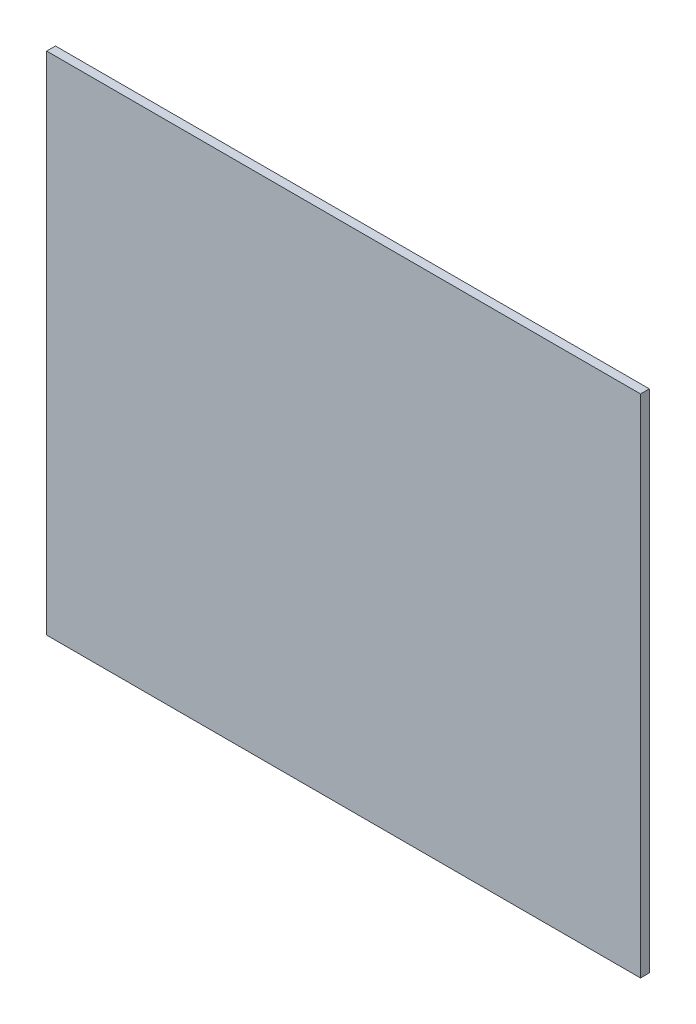
SolidWorks part; units mm, degrees
ref_plane "Front Plane" through (0, 0, 0) normal (0, 0, 1) x (1, 0, 0)
ref_plane "Top Plane" through (0, 0, 0) normal (0, 1, 0) x (1, 0, 0)
ref_plane "Right Plane" through (0, 0, 0) normal (1, 0, 0) x (0, 0, -1)
sketch "Sketch1" plane through (0, 0, 0) normal (0, 0, 1) x (1, 0, 0)
  line L1 (-135, 115) -> (135, 115)
  line L2 (-135, 115) -> (-135, -115)
  line L3 (-135, -115) -> (135, -115)
  line L4 (135, 115) -> (135, -115)
  line L5 (-135, 115) -> (135, -115) construction
  line L6 (-135, -115) -> (135, 115) construction
  point P0 (0, 0)
  dimension "D1" = 270
  dimension "D2" = 230
extrude "Boss-Extrude1" add sketch "Sketch1" along normal blind 4
